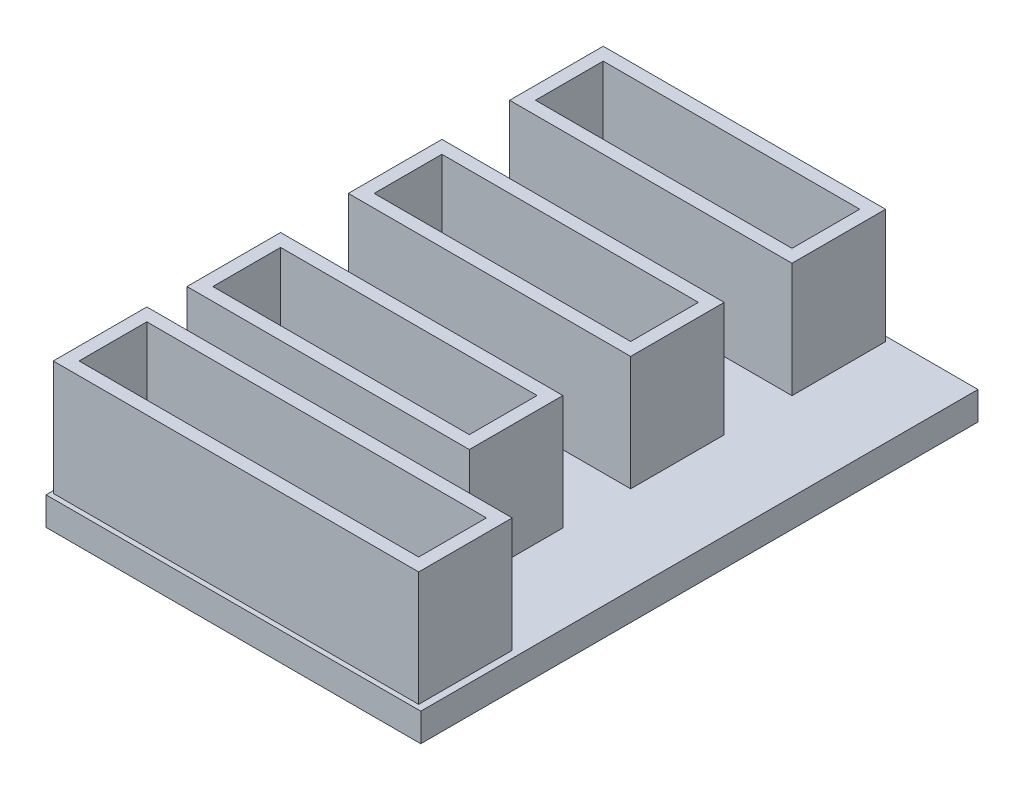
SolidWorks part; units mm, degrees
ref_plane "Front Plane" through (0, 0, 0) normal (0, 0, 1) x (1, 0, 0)
ref_plane "Top Plane" through (0, 0, 0) normal (0, 1, 0) x (1, 0, 0)
ref_plane "Right Plane" through (0, 0, 0) normal (1, 0, 0) x (0, 0, -1)
sketch "Sketch2" plane through (0, 0, 0) normal (0, 1, 0) x (1, 0, 0)
  line L1 (-11.615, 17.27) -> (11.615, 17.27)
  line L2 (-11.615, 17.27) -> (-11.615, -17.27)
  line L3 (-11.615, -17.27) -> (11.615, -17.27)
  line L4 (11.615, 17.27) -> (11.615, -17.27)
  line L5 (-11.615, 17.27) -> (11.615, -17.27) construction
  line L6 (-11.615, -17.27) -> (11.615, 17.27) construction
  point P0 (0, 0)
  dimension "D1" = 34.54
  dimension "D2" = 23.23
extrude "Boss-Extrude1" add sketch "Sketch2" against normal blind 1.75
sketch "Sketch3" plane through (0, 0, 0) normal (0, 1, 0) x (1, 0, 0)
  line L1 (-11.315, 16.97) -> (6.185, 16.97)
  line L2 (-11.315, 16.97) -> (-11.315, 11.17)
  line L3 (-11.315, 11.17) -> (6.185, 11.17)
  line L4 (11.615, -17.27) -> (11.615, 17.27)
  line L5 (11.615, 17.27) -> (-11.615, 17.27)
  line L6 (-11.615, 17.27) -> (-11.615, -17.27)
  line L7 (-11.615, -17.27) -> (11.615, -17.27)
  line L8 (11.615, -17.27) -> (11.615, 17.27) construction
  line L9 (11.615, 17.27) -> (-11.615, 17.27) construction
  line L10 (-11.615, 17.27) -> (-11.615, -17.27) construction
  line L11 (-11.615, -17.27) -> (11.615, -17.27) construction
  line L12 (6.185, 16.97) -> (6.185, 11.17)
  dimension "D2" = 5.8
  dimension "D3" = 17.5
  dimension "D4" = 0.3
  dimension "D5" = 0.3
  dimension "D1" = 0
extrude "Boss-Extrude2" add sketch "Sketch3" along normal blind 7.11 separate body
shell "Shell2" thickness 0.8
pattern_linear "LPattern1" count 3 spacing 10 along (0, 0, 1) of "Boss-Extrude2"
sketch "Sketch4" plane through (0, 0, 0) normal (0, 1, 0) x (1, 0, 0)
  line L1 (-11.465, -11.17) -> (11.185, -11.17)
  line L2 (-11.465, -11.17) -> (-11.465, -16.97)
  line L3 (-11.465, -16.97) -> (11.185, -16.97)
  line L4 (11.185, -11.17) -> (11.185, -16.97)
  line L8 (11.615, -17.27) -> (11.615, 17.27)
  line L9 (11.615, 17.27) -> (-11.615, 17.27)
  line L10 (-11.615, 17.27) -> (-11.615, -17.27)
  line L11 (-11.615, -17.27) -> (11.615, -17.27)
  line L12 (11.615, -17.27) -> (11.615, 17.27) construction
  line L13 (11.615, 17.27) -> (-11.615, 17.27) construction
  line L14 (-11.615, 17.27) -> (-11.615, -17.27) construction
  line L15 (-11.615, -17.27) -> (11.615, -17.27) construction
  line L16 (-11.315, 16.97) -> (-11.315, 11.17)
  line L17 (-11.315, 11.17) -> (6.185, 11.17)
  line L18 (6.185, 11.17) -> (6.185, 16.97)
  line L19 (6.185, 16.97) -> (-11.315, 16.97)
  line L20 (-11.315, 16.97) -> (-11.315, 11.17) construction
  line L21 (-11.315, 11.17) -> (6.185, 11.17) construction
  line L22 (6.185, 11.17) -> (6.185, 16.97) construction
  line L23 (6.185, 16.97) -> (-11.315, 16.97) construction
  dimension "D5" = 0.3
  dimension "D1" = 0
  dimension "D3" = 0.3
  dimension "D6" = 0.3
  dimension "D4" = 22.65
  dimension "D2" = 0
extrude "Boss-Extrude3" add sketch "Sketch4" along normal blind 7.11 separate body
shell "Shell3" thickness 0.8
shell "Shell4" thickness 0.8
shell "Shell5" thickness 0.8
equation "\"D5@Sketch3\"=\"D4@Sketch3\""
equation "\"D5@Sketch4\"=\"D3@Sketch4\""
equation "\"D6@Sketch4\"=\"D3@Sketch4\""
